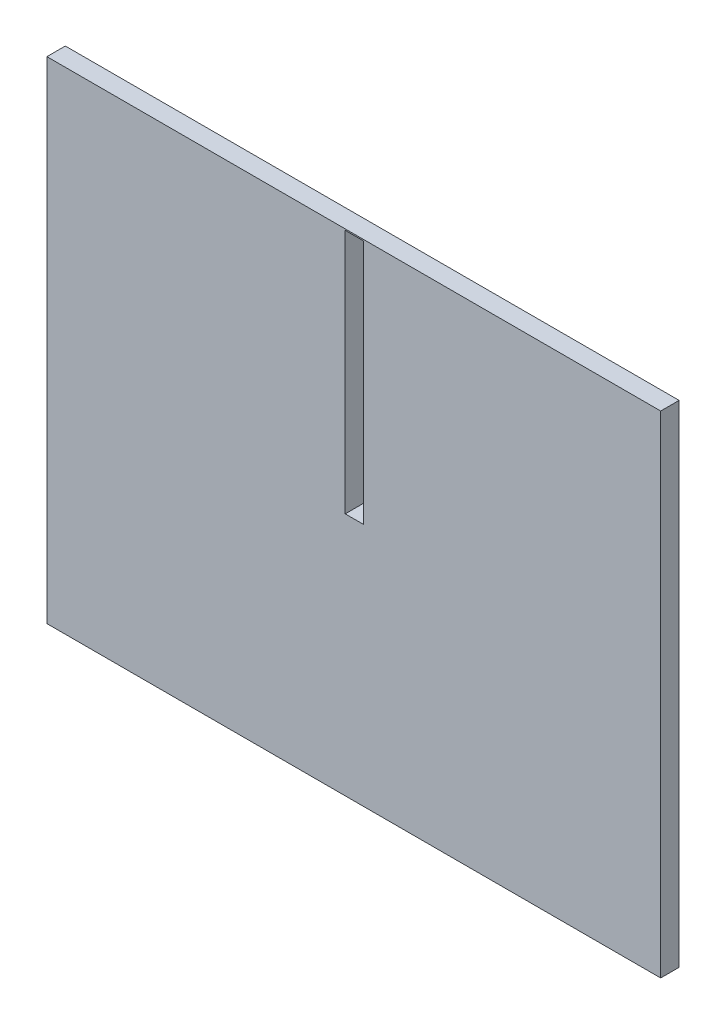
SolidWorks part; units mm, degrees
ref_plane "Front Plane" through (0, 0, 0) normal (0, 0, 1) x (1, 0, 0)
ref_plane "Top Plane" through (0, 0, 0) normal (0, 1, 0) x (1, 0, 0)
ref_plane "Right Plane" through (0, 0, 0) normal (1, 0, 0) x (0, 0, -1)
sketch "Sketch1" plane through (0, 0, 0) normal (0, 0, 1) x (1, 0, 0)
  line L1 (-50, -40) -> (50, -40)
  line L2 (-50, -40) -> (-50, 40)
  line L3 (-50, 40) -> (50, 40)
  line L4 (50, -40) -> (50, 40)
  line L5 (-50, -40) -> (50, 40) construction
  line L6 (-50, 40) -> (50, -40) construction
  point P0 (0, 0)
  dimension "D1" = 100
  dimension "D2" = 80
extrude "Boss-Extrude1" add sketch "Sketch1" along normal blind 3 contours L3 L4 L1 L2
sketch "Sketch2" plane through (0, 0, 3) normal (0, 0, 1) x (1, 0, 0)
  line L2 (1.6051, -0.2101) -> (1.6051, 39.7899)
  line L3 (-1.3949, -0.2101) -> (-1.3949, 39.7899)
  line L4 (-1.3949, -0.2101) -> (1.6051, -0.2101)
  line L5 (-1.3949, 39.7899) -> (1.6051, 39.7899)
extrude "Cut-Extrude1" cut sketch "Sketch2" against normal blind 13 and the other way blind 22 contours L5 L2 L4 L3
